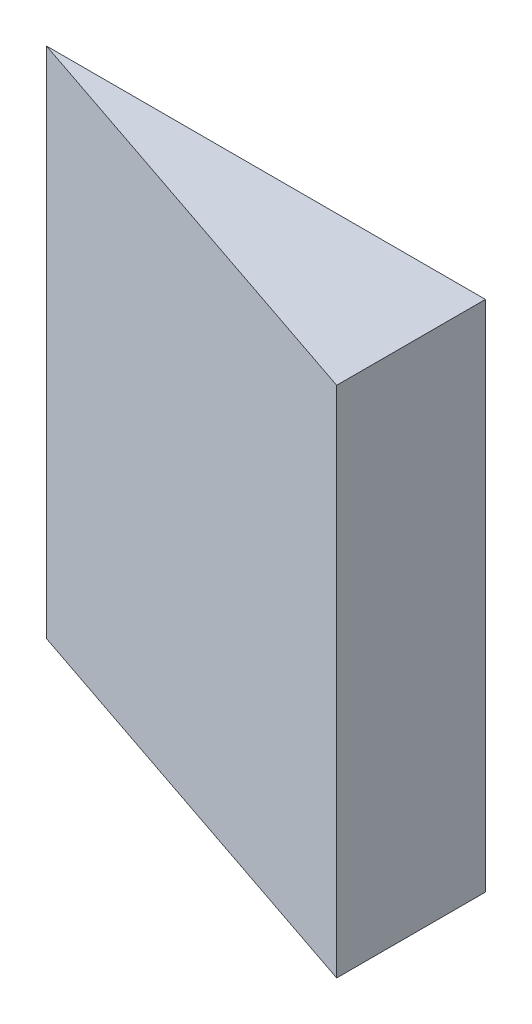
SolidWorks part; units mm, degrees
ref_plane "Front Plane" through (0, 0, 0) normal (0, 0, 1) x (1, 0, 0)
ref_plane "Top Plane" through (0, 0, 0) normal (0, 1, 0) x (1, 0, 0)
ref_plane "Right Plane" through (0, 0, 0) normal (1, 0, 0) x (0, 0, -1)
sketch "Sketch1" plane through (0, 0, 0) normal (0, 1, 0) x (1, 0, 0)
  line L0 (-9.9029, 34.1908) -> (65.0271, 34.1908)
  line L1 (65.0271, 34.1908) -> (65.0271, 8.7908)
  line L2 (-9.9029, 34.1908) -> (65.0271, 8.7908)
extrude "Boss-Extrude1" add sketch "Sketch1" along normal blind 87.63 contours L0 L1 L2
